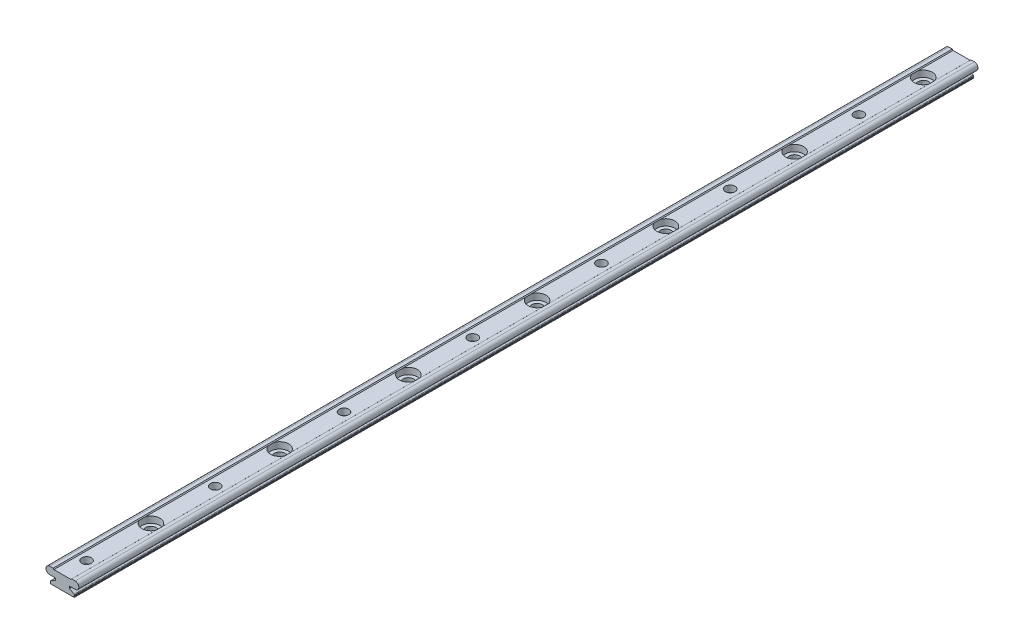
SolidWorks part; units mm, degrees
material "AISI 304"
ref_plane "Front" through (0, 0, 0) normal (0, 0, 1) x (1, 0, 0)
ref_plane "Top" through (0, 0, 0) normal (0, 1, 0) x (1, 0, 0)
ref_plane "Right" through (0, 0, 0) normal (1, 0, 0) x (0, 0, -1)
sketch "Sketch1" plane through (0, 0, 0) normal (0, 0, 1) x (1, 0, 0)
  line L0 (-7.925, 9.2) -> (-5.8, 9.2)
  line L1 (-7.925, 4.65) -> (-4.45, 4.65)
  line L2 (-4.45, 4.65) -> (-4.45, 3.3609)
  line L3 (7.5, 1.3067) -> (7.5, 0.254)
  line L4 (7.246, 0) -> (-7.246, 0)
  line L5 (-7.5, 0.254) -> (-7.5, 1.3067)
  line L6 (-4.45, 3.3609) -> (-7.246, 1.7466)
  line L7 (7.925, 4.65) -> (4.45, 4.65)
  line L8 (-15.492, 16) -> (-8.5, 16) construction
  line L9 (16, 15.492) -> (16, 11.4) construction
  line L10 (15.492, 1.9) -> (8.7804, 1.9) construction
  line L11 (-15.492, 1.9) -> (-8.7804, 1.9) construction
  line L12 (-16, 2.408) -> (-16, 6.6) construction
  line L13 (-16, 11.4) -> (-15.746, 11.4) construction
  line L14 (-15.746, 11.4) -> (-15.746, 6.6) construction
  line L15 (-15.746, 6.6) -> (-16, 6.6) construction
  line L16 (16, 11.4) -> (15.746, 11.4) construction
  line L17 (15.746, 11.4) -> (15.746, 6.6) construction
  line L18 (15.746, 6.6) -> (16, 6.6) construction
  line L19 (-16, 11.4) -> (-16, 15.492) construction
  line L20 (16, 6.6) -> (16, 2.408) construction
  line L21 (4.45, 4.65) -> (4.45, 3.3609)
  line L22 (4.45, 3.3609) -> (7.246, 1.7466)
  line L23 (-5.8, 9.2) -> (-5.2822, 8.7)
  line L24 (-5.2822, 8.7) -> (5.2822, 8.7)
  line L25 (5.2822, 8.7) -> (5.8, 9.2)
  line L26 (5.8, 9.2) -> (7.925, 9.2)
  line L27 (-8.7804, 1.9) -> (-6.35, 3.3032) construction
  line L28 (-6.35, 3.3032) -> (-6.35, 4.6) construction
  line L29 (7.5, 0) -> (7.5, 1.6) construction
  line L30 (-7.925, 9.25) -> (-5.3, 9.25) construction
  line L31 (-5.3, 9.25) -> (-5.3, 9.7) construction
  line L32 (-5.3, 9.7) -> (5.3, 9.7) construction
  line L33 (5.3, 9.7) -> (5.3, 9.25) construction
  line L34 (5.3, 9.25) -> (7.925, 9.25) construction
  line L35 (7.925, 4.6) -> (6.35, 4.6) construction
  line L36 (-7.925, 4.6) -> (-6.35, 4.6) construction
  line L39 (6.35, 4.6) -> (6.35, 3.3032) construction
  line L42 (6.35, 3.3032) -> (8.7804, 1.9) construction
  line L43 (-8.5, 16) -> (-8.5, 15.746) construction
  line L46 (-8.5, 15.746) -> (-3.7, 15.746) construction
  line L47 (-3.7, 15.746) -> (-3.7, 16) construction
  line L48 (3.7, 16) -> (3.7, 15.746) construction
  line L49 (3.7, 15.746) -> (8.5, 15.746) construction
  line L50 (8.5, 15.746) -> (8.5, 16) construction
  line L51 (-3.7, 16) -> (3.7, 16) construction
  line L52 (8.5, 16) -> (15.492, 16) construction
  arc A0 (-7.925, 9.2) -> (-7.925, 4.65) centre (-7.925, 6.925) ccw
  arc A1 (7.925, 9.2) -> (7.925, 4.65) centre (7.925, 6.925) cw
  arc A2 (-7.5, 1.3067) -> (-7.246, 1.7466) centre (-6.992, 1.3067) cw
  arc A3 (7.5, 1.3067) -> (7.246, 1.7466) centre (6.992, 1.3067) ccw
  arc A4 (15.492, 1.9) -> (16, 2.408) centre (15.492, 2.408) ccw construction
  arc A5 (16, 15.492) -> (15.492, 16) centre (15.492, 15.492) ccw construction
  arc A6 (-15.492, 1.9) -> (-16, 2.408) centre (-15.492, 2.408) cw construction
  arc A7 (-16, 15.492) -> (-15.492, 16) centre (-15.492, 15.492) cw construction
  arc A8 (-7.246, 0) -> (-7.5, 0.254) centre (-7.246, 0.254) cw
  arc A9 (7.246, 0) -> (7.5, 0.254) centre (7.246, 0.254) ccw
  arc A10 (-7.925, 9.25) -> (-7.925, 4.6) centre (-7.925, 6.925) ccw construction
  arc A11 (7.925, 9.25) -> (7.925, 4.6) centre (7.925, 6.925) cw construction
  point P2 (0, 9.7)
  point P7 (0, 8.7)
  point P26 (-10.2, 6.925)
  point P27 (10.2, 6.925)
  point P35 (0, 16)
  point P39 (-7.78, 6.31)
  point P40 (-5.45, 6.31)
  point P42 (-7.78, 13.45)
  point P43 (-5.7798, 13.45)
  point P46 (5.7798, 13.45)
  point P47 (7.78, 13.45)
  point P49 (7.78, 6.31)
  point P50 (5.45, 6.31)
  dimension "D7" = 0.508
  dimension "D3" = 0.254
  dimension "D5" = 0.05
  dimension "D1" = 0.254
  dimension "Rail Wd" = 15
  dimension "Rail Ht" = 9.2
  dimension "D2" = 30
  dimension "Oall Rail Wd" = 20.4
  dimension "Oall Ht" = 16
  dimension "Rail Offset" = 1.6
  dimension "Side Groove Offset" = 4.7
  dimension "Rail Neck Wd" = 8.9
  dimension "D4" = 136
  dimension "Rail Nose Thickness" = 4.55
  dimension "Rail Trough Dp" = 0.5
  dimension "Rail Trough Wd" = 11.6
  dimension "Side Groove Ht" = 4.8
  dimension "Carriage Trough Wd" = 10.6
  dimension "Carriage Trough Dp" = 0.5
  dimension "Top Groove Offset" = 7.5
  dimension "Oall Wd" = 32
  dimension "Carriage Ht" = 14.1
  dimension "Carriage Neck Wd" = 12.7
  dimension "Angle Offset" = 0.9
extrude "Boss-Extrude1" add sketch "Sketch1" along normal mid plane 670
sketch "Sketch4" plane through (0, 0, 0) normal (0, 0, 1) x (1, 0, 0)
  line L0 (7.5, 0.254) -> (7.5, 1.3067) construction
  line L1 (7.5, 0.635) -> (7.246, 0.635)
  line L2 (7.5, 0.635) -> (7.5, 1.016)
  line L3 (7.5, 1.016) -> (7.246, 1.016)
  line L4 (7.246, 0.635) -> (7.246, 1.016)
  line L5 (-7.246, 0) -> (7.246, 0) construction
  dimension "Notch Offset" = 0.635
  dimension "D2" = 0.254
  dimension "D3" = 0.381
extrude "Cut-Extrude1" cut sketch "Sketch4" against normal through all and the other way through all
sketch "Sketch2" plane through (0, 0, 0) normal (1, 0, 0) x (0, 0, -1)
  line L0 (-323, 8.7) -> (-323, 4.7)
  line L1 (-323, 4.7) -> (-321.75, 4.7)
  line L2 (-321.75, 4.7) -> (-321.75, 0)
  line L3 (-321.75, 0) -> (-320, 0)
  line L4 (-320, 0) -> (-320, 8.7)
  line L5 (-320, 8.7) -> (-323, 8.7) construction
  line L6 (-335, 8.7) -> (335, 8.7) construction
  line L7 (-323, 8.7) -> (-317, 8.7) construction
  line L8 (-321.75, 0) -> (-318.25, 0) construction
  line L9 (-335, 0) -> (335, 0) construction
  line L10 (-335, 0) -> (335, 0) construction
  line L14 (-335, 9.2) -> (-335, 4.65) construction
  line L15 (-323, 8.7) -> (-323, 9.2)
  line L16 (-335, 9.2) -> (335, 9.2) construction
  line L17 (-323, 9.2) -> (-320, 9.2)
  line L18 (-320, 9.2) -> (-320, 8.7)
  dimension "Top Hole Dp" = 4
  dimension "Top Hole Dia" = 6
  dimension "Bottom Hole Dia" = 3.5
  dimension "Hole Offset" = 15
revolve "Cut-Revolve1" cut sketch "Sketch2" angle 360 mid plane about L4
pattern_linear "LPattern2" count 17 spacing 40 along (0, 0, -1) of "Cut-Revolve1"
sketch "Sketch3" plane through (0, 0, 0) normal (1, 0, 0) x (0, 0, -1)
  line L2 (-323, 4.7) -> (-323, 8.7)
  line L7 (-317, 4.7) -> (-317, 8.7)
  line L13 (-317, 4.7) -> (-323, 4.7) construction
  line L14 (-318.25, 0) -> (-318.25, 4.7) construction
  line L15 (-321.75, 4.7) -> (-321.75, 0) construction
  line L18 (-317, 4.7) -> (-323, 4.7)
  line L19 (-318.25, 0) -> (-318.25, 4.7)
  line L20 (-321.75, 4.7) -> (-321.75, 0)
  line L21 (-335, 8.7) -> (335, 8.7)
  line L22 (335, 4.65) -> (335, 9.2) construction
mirror "K15" [suppressed] about plane through (0, 0, 0) normal (1, 0, 0)
ref_plane "Plane1" through (0, 0, -210) normal (0, 0, -1) x (-1, 0, 0)
sketch "Sketch9" plane through (0, 8.7, 0) normal (0, 1, 0) x (1, 0, 0)
  line L0 (10.2, -335) -> (10.2, 335) construction
  line L1 (-10.2, 335) -> (10.2, 335)
  line L2 (-10.2, 335) -> (-10.2, 223.8)
  line L3 (-10.2, 223.8) -> (10.2, 223.8)
  line L4 (10.2, 335) -> (10.2, 223.8)
  line L5 (5.2822, -335) -> (-5.2822, -335) construction
  point P6 (0, 0)
  dimension "D1" = 558.8
extrude "Cut-Extrude2" cut sketch "Sketch9" against normal through all both and the other way through all
sketch "Sketch10" plane through (0, 8.7, 0) normal (0, 1, 0) x (1, 0, 0)
  circle A0 centre (0, 200) radius 5.6197
  dimension "D1" = 11.2395
extrude "Cut-Extrude3" cut sketch "Sketch10" against normal blind 3.9688
hole_wizard "1/4 Clearance Hole1" positions "Sketch11" profile "Sketch12" hole size "1/4" standard "ANSI Inch" end condition through all
sketch "Sketch11" plane through (0, 4.7313, 0) normal (0, 1, 0) x (1, 0, 0)
  point P0 (0, 200)
sketch "Sketch12" plane through (0, 4.7313, -200) normal (1, 0, 0) x (0, 0, 1)
  line L0 (0, 0) -> (0, 4.7313)
  line L1 (0, 4.7313) -> (3.3782, 4.7313)
  line L2 (3.3782, 4.7313) -> (3.3782, 0)
  line L5 (3.3782, 0) -> (0, 0)
  line L11 (0, -6.35) -> (0, 107.95) construction
  dimension "Thru Hole Dia." = 6.7564
  dimension "Thru Hole Depth" = 4.7313
pattern_linear "LPattern3" count 7 spacing 80 along (0, 0, 1) of "Cut-Extrude3", "1/4 Clearance Hole1"
